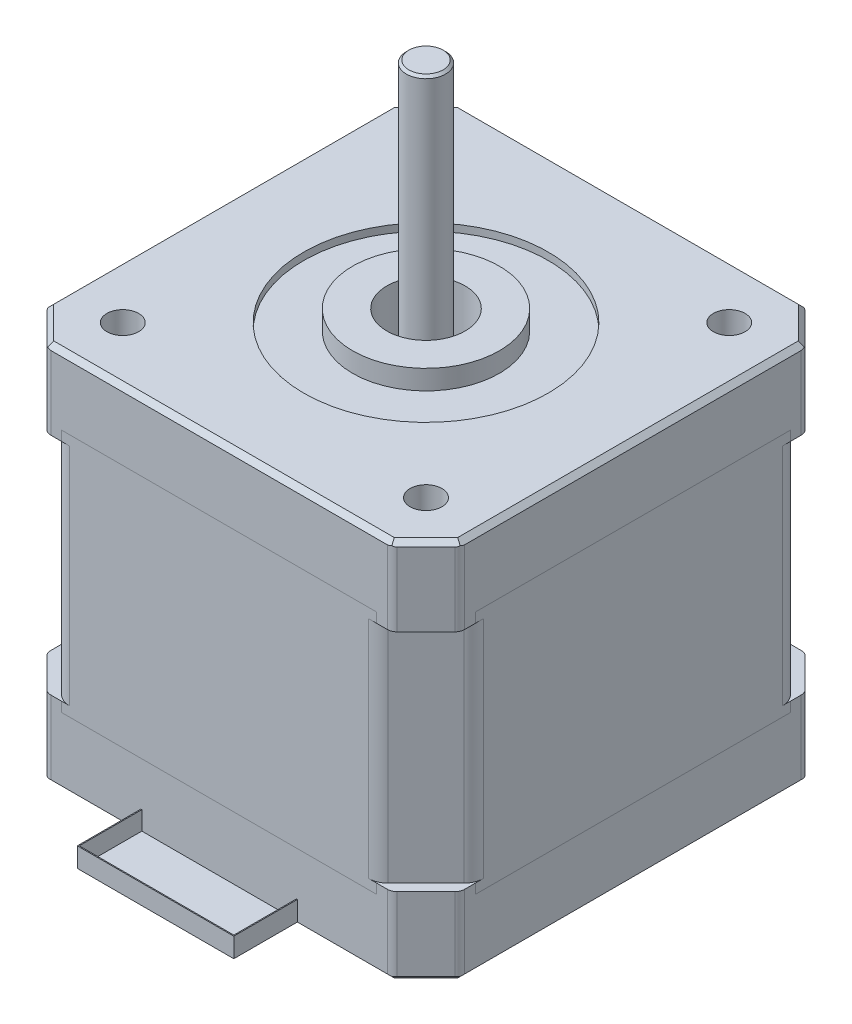
SolidWorks part; units mm, degrees
other "Markup1"
sketch "Sketch28"
ref_plane "Front Plane" through (0, 0, 0) normal (0, 0, 1) x (1, 0, 0)
ref_plane "Top Plane" through (0, 0, 0) normal (0, 1, 0) x (1, 0, 0)
ref_plane "Right Plane" through (0, 0, 0) normal (1, 0, 0) x (0, 0, -1)
sketch "Sketch1" plane through (0, 0, 0) normal (0, 1, 0) x (1, 0, 0)
  line L0 (-41.2413, 0) -> (21.15, 0) construction
  line L1 (0, -27.9894) -> (0, 21.15) construction
  line L2 (-21.15, -17.6145) -> (-21.15, 17.6145)
  line L3 (-21.15, 17.6145) -> (-17.6145, 21.15)
  line L4 (-17.6145, 21.15) -> (17.6145, 21.15)
  line L5 (17.6145, 21.15) -> (21.15, 17.6145)
  line L6 (21.15, 17.6145) -> (21.15, -17.6145)
  line L7 (21.15, -17.6145) -> (17.6145, -21.15)
  line L8 (17.6145, -21.15) -> (-17.6145, -21.15)
  line L9 (-17.6145, -21.15) -> (-21.15, -17.6145)
  dimension "D1" = 42.3
  dimension "D2" = 45
  dimension "D3" = 5
extrude "Boss-Extrude1" add sketch "Sketch1" against normal blind 8
sketch "Sketch2" plane through (0, 0, 0) normal (0, 1, 0) x (1, 0, 0)
  line L0 (-21.15, 0) -> (21.15, 0) construction
  line L1 (-21.15, 17.6145) -> (-21.15, -17.6145) construction
  line L2 (21.15, -17.6145) -> (21.15, 17.6145) construction
  line L3 (0, -21.15) -> (0, 21.15) construction
  line L4 (-17.6145, -21.15) -> (17.6145, -21.15) construction
  line L5 (17.6145, 21.15) -> (-17.6145, 21.15) construction
  circle A0 centre (-15.5, 15.5) radius 1.6248
  circle A1 centre (15.5, 15.5) radius 1.6248
  circle A2 centre (15.5, -15.5) radius 1.6248
  circle A3 centre (-15.5, -15.5) radius 1.6248
  dimension "D3" = 3.2495
  dimension "D1" = 31
  dimension "D2" = 31
extrude "Cut-Extrude1" cut sketch "Sketch2" against normal blind 6
chamfer "Chamfer1" distance 0.5 angle 45 8 edges at (-21.15, 0, 0) (-19.3822, 0, -19.3822) (0, 0, -21.15) (19.3822, 0, -19.3822) (21.15, 0, 0) (19.3822, 0, 19.3822) (0, 0, 21.15) (-19.3822, 0, 19.3822)
sketch "Sketch3" plane through (21.15, 0, 0) normal (1, 0, 0) x (0, 0, -1)
  line L0 (-16.1145, -8) -> (16.1145, -8)
  line L1 (-17.6145, -8) -> (17.6145, -8) construction
  line L2 (-16.1145, -8) -> (-16.1145, -7)
  line L3 (-16.1145, -7) -> (16.1145, -7)
  line L4 (16.1145, -7) -> (16.1145, -8)
  dimension "D1" = 1.5
  dimension "D2" = 1.5
  dimension "D3" = 1
extrude "Cut-Extrude2" cut sketch "Sketch3" against normal through all
sketch "Sketch4" plane through (0, 0, 21.15) normal (0, 0, 1) x (1, 0, 0)
  line L0 (-16.1145, -8) -> (-16.1145, -7)
  line L1 (-17.6145, -8) -> (17.6145, -8) construction
  line L2 (-16.1145, -7) -> (16.1145, -7)
  line L3 (16.1145, -7) -> (16.1145, -8)
  line L4 (16.1145, -8) -> (-16.1145, -8)
  line L5 (-17.6145, -8) -> (-17.6145, -0.5) construction
  line L6 (17.6145, -8) -> (17.6145, -0.5) construction
  dimension "D1" = 1.5
  dimension "D2" = 1.5
  dimension "D3" = 1
extrude "Cut-Extrude3" cut sketch "Sketch4" against normal through all
sketch "Sketch5" plane through (0, -8, 0) normal (0, -1, 0) x (1, 0, 0)
  line L0 (-21.15, 16.1145) -> (-16.1145, 21.15)
  line L4 (-21.15, 16.1145) -> (-16.1145, 16.1145)
  line L5 (-16.1145, 16.1145) -> (-16.1145, 21.15)
extrude "Cut-Extrude4" cut sketch "Sketch5" against normal blind 1
mirror "Mirror1" about plane through (0, 0, 0) normal (1, 0, 0) of "Cut-Extrude4"
mirror "Mirror2" about plane through (0, 0, 0) normal (0, 0, 1) of "Mirror1", "Cut-Extrude4"
sketch "Sketch6" plane through (0, -7, 0) normal (0, -1, 0) x (1, 0, 0)
  line L0 (-21.15, -16.1145) -> (-21.15, 16.1145)
  line L1 (-21.15, 16.1145) -> (-16.1145, 21.15)
  line L2 (-16.1145, 21.15) -> (16.1145, 21.15)
  line L3 (16.1145, 21.15) -> (21.15, 16.1145)
  line L4 (21.15, 16.1145) -> (21.15, -16.1145)
  line L5 (21.15, -16.1145) -> (16.1145, -21.15)
  line L6 (16.1145, -21.15) -> (-16.1145, -21.15)
  line L7 (-16.1145, -21.15) -> (-21.15, -16.1145)
extrude "Boss-Extrude2" add sketch "Sketch6" along normal blind 24
sketch "Sketch12" plane through (21.15, 0, 0) normal (1, 0, 0) x (0, 0, -1)
  line L0 (-16.1145, -8) -> (-16.1145, -7)
  line L1 (-16.1145, -7) -> (16.1145, -7)
  line L2 (16.1145, -7) -> (16.1145, -8)
  dimension "D1" = 1
split line "Split Line5"
sketch "Sketch13" plane through (0, 0, -21.15) normal (0, 0, -1) x (-1, 0, 0)
  line L0 (-16.1145, -8) -> (-16.1145, -7)
  line L1 (-16.1145, -7) -> (16.1145, -7)
  line L2 (16.1145, -7) -> (16.1145, -8)
  dimension "D1" = 1
split line "Split Line6"
sketch "Sketch14" plane through (-21.15, 0, 0) normal (-1, 0, 0) x (0, 0, 1)
  line L0 (-16.1145, -8) -> (-16.1145, -7)
  line L1 (-16.1145, -7) -> (16.1145, -7)
  line L2 (16.1145, -7) -> (16.1145, -8)
  dimension "D1" = 1
split line "Split Line7"
sketch "Sketch15" plane through (0, 0, 21.15) normal (0, 0, 1) x (1, 0, 0)
  line L0 (-16.1145, -8) -> (-16.1145, -7)
  line L1 (-16.1145, -7) -> (16.1145, -7)
  line L2 (16.1145, -7) -> (16.1145, -8)
  dimension "D1" = 1
split line "Split Line8"
sketch "Sketch16" plane through (0, -31, 0) normal (0, -1, 0) x (1, 0, 0)
  line L0 (-21.15, -17.6145) -> (-21.15, 17.6145)
  line L1 (-21.15, 17.6145) -> (-17.6145, 21.15)
  line L2 (-17.6145, 21.15) -> (17.6145, 21.15)
  line L3 (17.6145, 21.15) -> (21.15, 17.6145)
  line L4 (21.15, 17.6145) -> (21.15, -17.6145)
  line L5 (21.15, -17.6145) -> (17.6145, -21.15)
  line L6 (17.6145, -21.15) -> (-17.6145, -21.15)
  line L7 (-17.6145, -21.15) -> (-21.15, -17.6145)
extrude "Boss-Extrude4" add sketch "Sketch16" along normal blind 8
sketch "Sketch17" plane through (0, 0, 21.15) normal (0, 0, 1) x (1, 0, 0)
  line L0 (-16.1145, -31) -> (-16.1145, -32)
  line L1 (-16.1145, -32) -> (16.1145, -32)
  line L2 (16.1145, -32) -> (16.1145, -31)
  dimension "D1" = 1
split line "Split Line9"
sketch "Sketch18" plane through (21.15, 0, 0) normal (1, 0, 0) x (0, 0, -1)
  line L0 (-16.1145, -31) -> (-16.1145, -32)
  line L1 (-16.1145, -32) -> (16.1145, -32)
  line L2 (16.1145, -32) -> (16.1145, -31)
  dimension "D1" = 1
split line "Split Line10"
sketch "Sketch19" plane through (0, 0, -21.15) normal (0, 0, -1) x (-1, 0, 0)
  line L0 (-16.1145, -31) -> (-16.1145, -32)
  line L1 (-16.1145, -32) -> (16.1145, -32)
  line L2 (16.1145, -32) -> (16.1145, -31)
  dimension "D1" = 1
split line "Split Line11"
sketch "Sketch20" plane through (-21.15, 0, 0) normal (-1, 0, 0) x (0, 0, 1)
  line L0 (-16.1145, -31) -> (-16.1145, -32)
  line L1 (-16.1145, -32) -> (16.1145, -32)
  line L2 (16.1145, -32) -> (16.1145, -31)
  dimension "D1" = 1
split line "Split Line12"
sketch "Sketch22" plane through (0, 0, 21.15) normal (0, 0, 1) x (1, 0, 0)
  line L0 (-8, -39) -> (8, -39)
  line L1 (17.6145, -39) -> (-17.6145, -39) construction
  line L2 (8, -39) -> (8, -36.5)
  line L3 (8, -36.5) -> (-8, -36.5)
  line L4 (-8, -36.5) -> (-8, -39)
  line L5 (0, 0) -> (0, -39) construction
  dimension "D1" = 16
  dimension "D2" = 2.5
extrude "Boss-Extrude5" add sketch "Sketch22" along normal blind 6.5
chamfer "Chamfer3" distance 0.5 angle 45 12 edges at (-21.15, -39, 0) (-19.3822, -39, 19.3822) (-12.8072, -39, 21.15) (-8, -39, 24.4) (0, -39, 27.65) (8, -39, 24.4) (12.8072, -39, 21.15) (19.3822, -39, 19.3822) (21.15, -39, 0) (19.3822, -39, -19.3822) (0, -39, -21.15) (-19.3822, -39, -19.3822)
sketch "Sketch23" plane through (0, -36.5, 0) normal (0, 1, 0) x (1, 0, 0)
  line L0 (-8, -27.65) -> (-8, -21.15) construction
  line L1 (-7.9, -21.15) -> (7.9, -21.15)
  line L2 (-7.9, -21.15) -> (-7.9, -27.55)
  line L3 (-7.9, -27.55) -> (7.9, -27.55)
  line L4 (7.9, -21.15) -> (7.9, -27.55)
  line L5 (-7.9, -21.15) -> (7.9, -27.55) construction
  line L6 (-7.9, -27.55) -> (7.9, -21.15) construction
  line L7 (8, -27.65) -> (8, -21.15) construction
  line L8 (8, -27.65) -> (-8, -27.65) construction
  line L10 (8, -21.15) -> (-8, -21.15) construction
  point P0 (0, -24.35)
  dimension "D1" = 0.1
  dimension "D2" = 0.1
  dimension "D3" = 0.1
extrude "Cut-Extrude5" cut sketch "Sketch23" against normal blind 1.9
sketch "Sketch24" plane through (0, 0, 0) normal (0, 1, 0) x (1, 0, 0)
  circle A0 centre (0, 0) radius 12.5
  dimension "D1" = 25
extrude "Cut-Extrude6" cut sketch "Sketch24" against normal blind 0.75
sketch "Sketch25" plane through (0, -0.75, 0) normal (0, 1, 0) x (1, 0, 0)
  circle A0 centre (0, 0) radius 7.5
  dimension "D1" = 15
extrude "Boss-Extrude6" add sketch "Sketch25" along normal blind 2
sketch "Sketch26" plane through (0, 1.25, 0) normal (0, 1, 0) x (1, 0, 0)
  circle A0 centre (0, 0) radius 4
  dimension "D1" = 8
extrude "Cut-Extrude7" cut sketch "Sketch26" against normal blind 5
sketch "Sketch27" plane through (0, -3.75, 0) normal (0, 1, 0) x (1, 0, 0)
  circle A0 centre (0, 0) radius 2
  dimension "D1" = 4
extrude "Boss-Extrude7" add sketch "Sketch27" along normal blind 27
chamfer "Chamfer5" distance 0.25 angle 45 1 edges at (0, 23.25, 2)
fillet "Fillet1" radius 2 8 edges at (-16.1145, -19.5, 21.15) (-21.15, -19.5, 16.1145) (-21.15, -19.5, -16.1145) (-16.1145, -19.5, -21.15) (21.15, -19.5, -16.1145) (16.1145, -19.5, -21.15) (21.15, -19.5, 16.1145) (16.1145, -19.5, 21.15)
fillet "Fillet3" radius 1 8 edges at (-17.6145, -4.25, 21.15) (-21.15, -4.25, 17.6145) (-21.15, -4.25, -17.6145) (-17.6145, -4.25, -21.15) (17.6145, -4.25, -21.15) (21.15, -4.25, -17.6145) (17.6145, -4.25, 21.15) (21.15, -4.25, 17.6145)
fillet "Fillet4" radius 1 8 edges at (-21.15, -34.75, -17.6145) (-21.15, -34.75, 17.6145) (-17.6145, -34.75, 21.15) (17.6145, -34.75, 21.15) (21.15, -34.75, 17.6145) (21.15, -34.75, -17.6145) (17.6145, -34.75, -21.15) (-17.6145, -34.75, -21.15)
